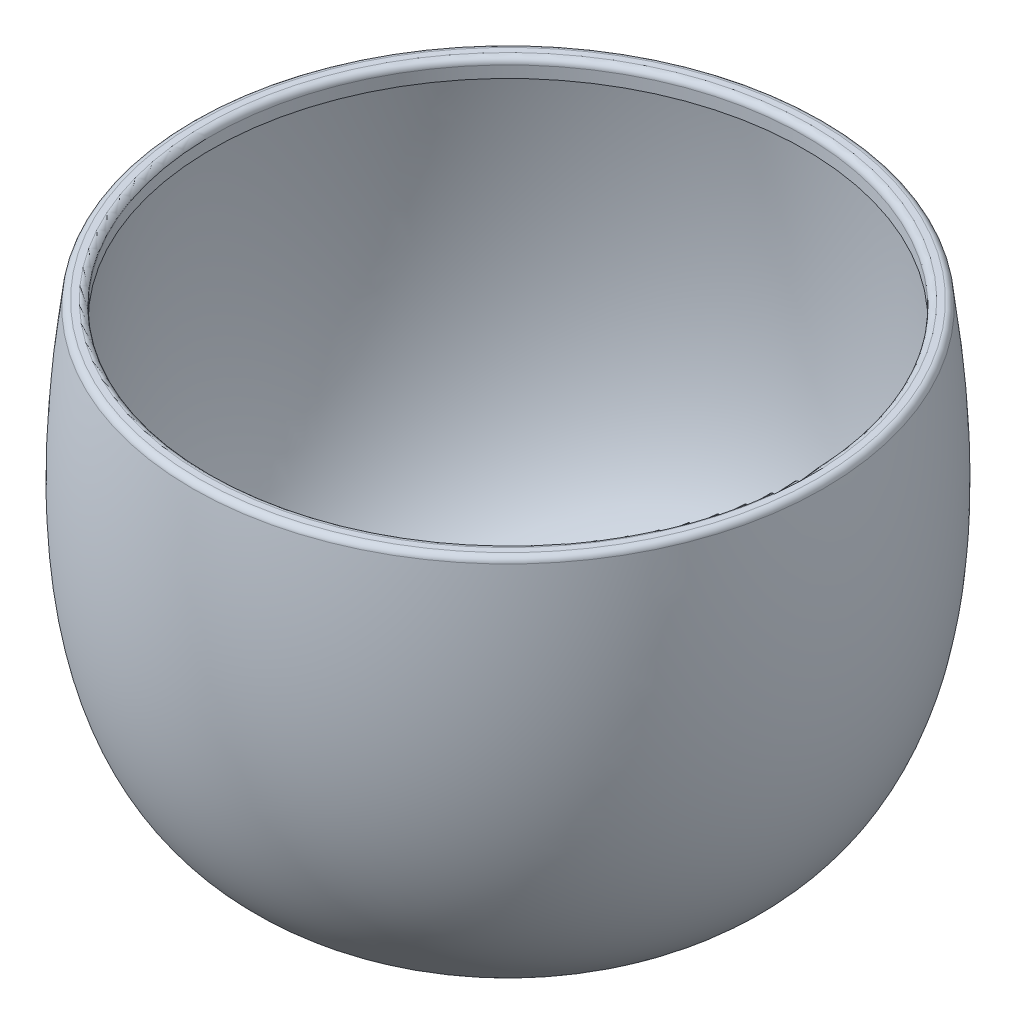
SolidWorks part; units mm, degrees
ref_plane "Front Plane" through (0, 0, 0) normal (0, 0, 1) x (1, 0, 0)
ref_plane "Top Plane" through (0, 0, 0) normal (0, 1, 0) x (1, 0, 0)
ref_plane "Right Plane" through (0, 0, 0) normal (1, 0, 0) x (0, 0, -1)
sketch "Sketch2" plane through (0, 0, 0) normal (1, 0, 0) x (0, 0, -1)
  line L0 (-9.0283, -5.0313) -> (16.3717, -5.0313)
  line L1 (-9.0283, -5.0313) -> (-9.0283, 58.4687)
  line L2 (-9.0283, 58.4687) -> (35.4217, 58.4687)
  spline S0 degree 2 poles (35.4217, 58.4687) (42.976, 3.7635) (16.3717, -5.0313) knots 0 0 0 0.722998 0.722998 0.722998
revolve "Revolve1" add sketch "Sketch2" angle 360 about L1
sketch "Sketch4" plane through (0, 58.4687, 0) normal (0, 1, 0) x (1, 0, 0)
  circle A0 centre (0, -9.0283) radius 41.91
shell "Shell2" thickness 2.54
extrude "Cut-Extrude3" cut sketch "Sketch4" against normal blind 2.54
fillet "Fillet9" radius 0.889 2 edges at (0, 58.4687, 50.9383) (0, 58.4687, -35.4217)
fillet "Fillet10" radius 0.254 1 edges at (0, 55.9287, -33.1968)
